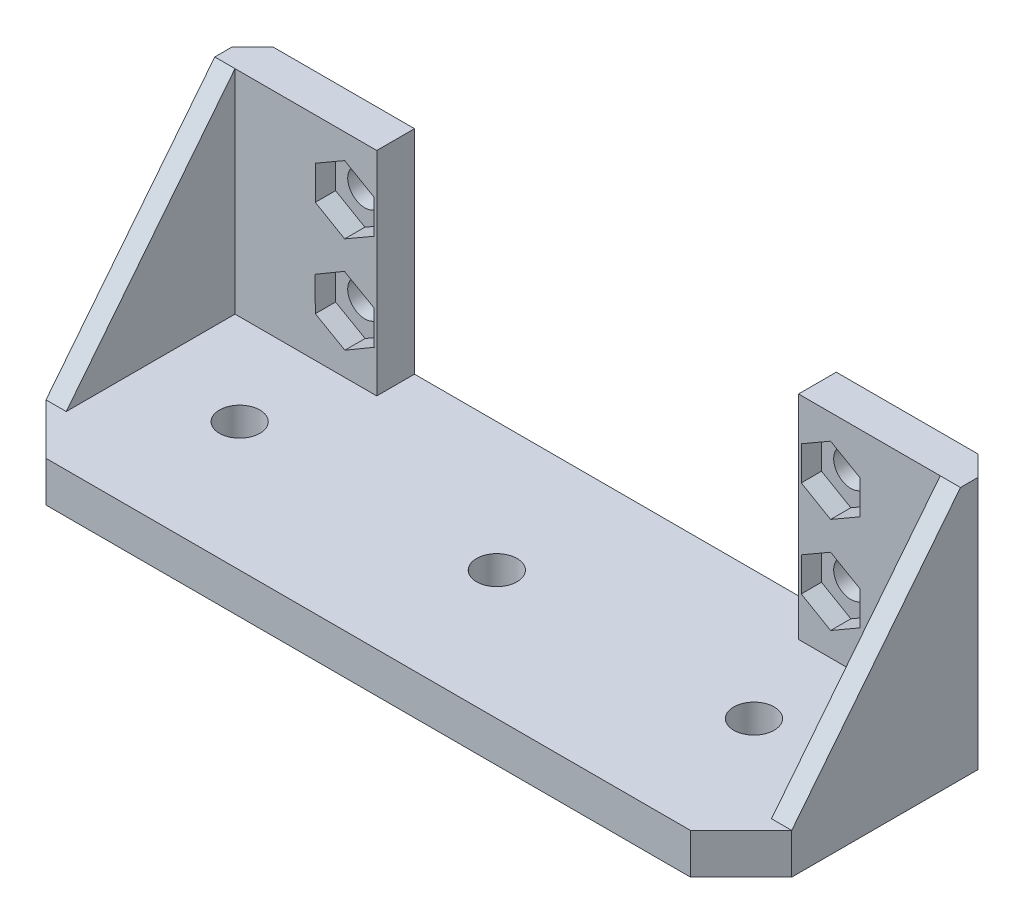
SolidWorks part; units mm, degrees
ref_plane "Front Plane" through (0, 0, 0) normal (0, 0, 1) x (1, 0, 0)
ref_plane "Top Plane" through (0, 0, 0) normal (0, 1, 0) x (1, 0, 0)
ref_plane "Right Plane" through (0, 0, 0) normal (1, 0, 0) x (0, 0, -1)
sketch "Sketch1" plane through (0, 0, 0) normal (0, 1, 0) x (1, 0, 0)
  line L1 (-36.83, 12.7) -> (36.83, 12.7)
  line L2 (-36.83, 12.7) -> (-36.83, -12.7)
  line L3 (-36.83, -12.7) -> (36.83, -12.7)
  line L4 (36.83, 12.7) -> (36.83, -12.7)
  line L5 (-36.83, 12.7) -> (36.83, -12.7) construction
  line L6 (-36.83, -12.7) -> (36.83, 12.7) construction
  point P0 (0, 0)
  dimension "D1" = 73.66
  dimension "D2" = 25.4
extrude "Boss-Extrude1" add sketch "Sketch1" along normal blind 4
chamfer "Chamfer1" distance 5 angle 45 2 edges at (36.83, 2, 12.7) (-36.83, 2, 12.7)
sketch "Sketch2" plane through (0, 4, 0) normal (0, 1, 0) x (1, 0, 0)
  line L1 (-36.83, 12.7) -> (-20.83, 12.7)
  line L2 (-36.83, 12.7) -> (-36.83, 8.9715)
  line L3 (-36.83, 8.9715) -> (-20.83, 8.9715)
  line L4 (-20.83, 12.7) -> (-20.83, 8.9715)
  line L5 (36.83, 12.7) -> (20.83, 12.7)
  line L6 (36.83, 12.7) -> (36.83, 8.9715)
  line L7 (36.83, 8.9715) -> (20.83, 8.9715)
  line L8 (20.83, 12.7) -> (20.83, 8.9715)
  circle A0 centre (-25.4, 0) radius 2
  circle A1 centre (0, 0) radius 2
  circle A2 centre (25.4, 0) radius 2
  dimension "D1" = 4
  dimension "D2" = 4
  dimension "D3" = 4
  dimension "D4" = 25.4
  dimension "D5" = 25.4
  dimension "D6" = 16
  dimension "D7" = 16
extrude "Boss-Extrude2" add sketch "Sketch2" along normal blind 21
sketch "Sketch3" plane through (0, 25, 0) normal (0, 1, 0) x (1, 0, 0)
  circle A0 centre (-25.4, 0) radius 2
  circle A1 centre (0, 0) radius 2
  circle A2 centre (25.4, 0) radius 2
extrude "Cut-Extrude1" cut sketch "Sketch3" against normal blind 31
sketch "Sketch4" plane through (36.83, 0, 0) normal (1, 0, 0) x (0, 0, -1)
  line L0 (8.9715, 25) -> (-7.7, 4)
  line L1 (-7.7, 4) -> (8.9715, 4)
  line L2 (8.9715, 4) -> (8.9715, 25)
extrude "Boss-Extrude3" add sketch "Sketch4" against normal blind 2
sketch "Sketch5" plane through (-36.83, 0, 0) normal (-1, 0, 0) x (0, 0, 1)
  line L0 (-8.9715, 25) -> (7.7, 4)
  line L1 (7.7, 4) -> (-8.9715, 4)
  line L2 (-8.9715, 4) -> (-8.9715, 25)
extrude "Boss-Extrude4" add sketch "Sketch5" against normal blind 2
chamfer "Chamfer2" distance 2 angle 45 2 edges at (36.83, 12.5, -12.7) (-36.83, 12.5, -12.7)
sketch "Sketch7" plane through (0, 0, -8.9715) normal (0, 0, 1) x (1, 0, 0)
  line L0 (-31.83, 4) -> (31.83, 4) construction
  line L1 (-20.83, 25) -> (-20.83, 4) construction
  circle A0 centre (-24, 19.2) radius 1.7
  circle A1 centre (-24, 9.7) radius 1.7
  circle A2 centre (24, 19.2) radius 1.7
  circle A3 centre (24, 9.7) radius 1.7
  dimension "D1" = 3.4
  dimension "D2" = 3.4
  dimension "D3" = 3.4
  dimension "D4" = 3.4
  dimension "D5" = 9.5
  dimension "D6" = 9.5
  dimension "D7" = 5.7
  dimension "D8" = 5.7
  dimension "D9" = 48
  dimension "D10" = 48
  dimension "D11" = 3.17
  dimension "D12" = 3.17
extrude "Cut-Extrude2" cut sketch "Sketch7" against normal blind 12
sketch "Sketch8" plane through (0, 0, -8.9715) normal (0, 0, 1) x (1, 0, 0)
  line L0 (-20.83, 25) -> (-20.83, 4) construction
  line L1 (-21.1, 17.5257) -> (-21.1, 20.8743)
  line L2 (-21.1, 20.8743) -> (-24, 22.5486)
  line L3 (-24, 22.5486) -> (-26.9, 20.8743)
  line L4 (-26.9, 20.8743) -> (-26.9, 17.5257)
  line L5 (-26.9, 17.5257) -> (-24, 15.8514)
  line L6 (-24, 15.8514) -> (-21.1, 17.5257)
  line L7 (20.83, 25) -> (20.83, 4) construction
  line L8 (-21.1, 11.4) -> (-24.0222, 13.0615)
  line L9 (-24.0222, 13.0615) -> (-26.9222, 11.3615)
  line L10 (-26.9222, 11.3615) -> (-26.9, 8)
  line L11 (-26.9, 8) -> (-23.9778, 6.3385)
  line L12 (-23.9778, 6.3385) -> (-21.0778, 8.0385)
  line L13 (-21.0778, 8.0385) -> (-21.1, 11.4)
  line L14 (21.1, 20.8743) -> (21.1, 17.5257)
  line L15 (21.1, 17.5257) -> (24, 15.8514)
  line L16 (24, 15.8514) -> (26.9, 17.5257)
  line L17 (26.9, 17.5257) -> (26.9, 20.8743)
  line L18 (26.9, 20.8743) -> (24, 22.5486)
  line L19 (24, 22.5486) -> (21.1, 20.8743)
  line L21 (21.1, 11.3743) -> (21.1, 8.0257)
  line L22 (21.1, 8.0257) -> (24, 6.3514)
  line L23 (24, 6.3514) -> (26.9, 8.0257)
  line L24 (26.9, 8.0257) -> (26.9, 11.3743)
  line L25 (26.9, 11.3743) -> (24, 13.0486)
  line L26 (24, 13.0486) -> (21.1, 11.3743)
  circle A0 centre (-24, 19.2) radius 2.9 construction
  circle A1 centre (-24, 9.7) radius 2.9112 construction
  circle A2 centre (24, 19.2) radius 2.9 construction
  circle A3 centre (24, 9.7) radius 2.9 construction
  dimension "D1" = 0
  dimension "D2" = 5.8
  dimension "D3" = 0
  dimension "D4" = 5.8
  dimension "D5" = 5.8
  dimension "D6" = 0
extrude "Cut-Extrude3" cut sketch "Sketch8" against normal blind 2
